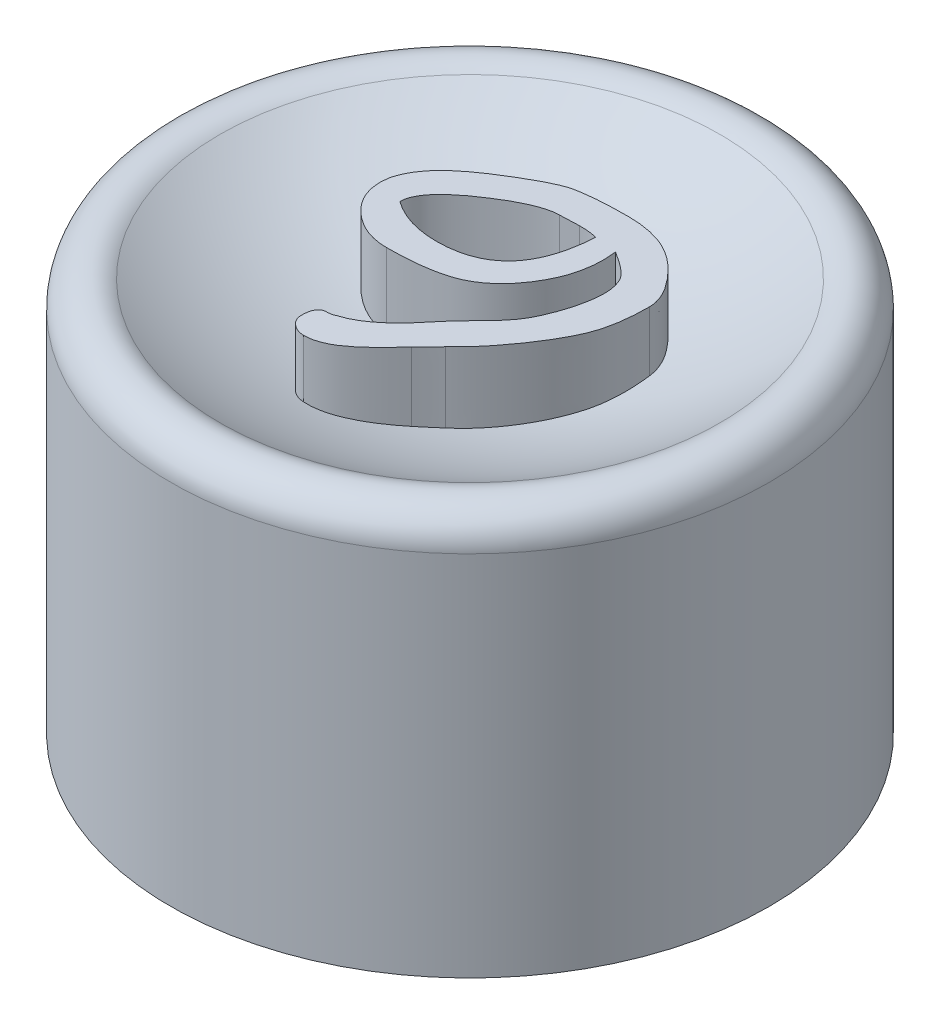
SolidWorks part; units mm, degrees
ref_plane "Front Plane" through (0, 0, 0) normal (0, 0, 1) x (1, 0, 0)
ref_plane "Top Plane" through (0, 0, 0) normal (0, 1, 0) x (1, 0, 0)
ref_plane "Right Plane" through (0, 0, 0) normal (1, 0, 0) x (0, 0, -1)
sketch "Sketch1" plane through (0, 0, 0) normal (0, 0, 1) x (1, 0, 0)
  line L0 (0, 0) -> (0, -66.4851) construction
  line L1 (55, 0) -> (-55, 0) construction
  line L2 (-1.5494, 0) -> (-1.5494, 3.048)
  line L3 (-1.5494, 3.048) -> (-0.762, 3.048)
  line L4 (-0.762, 3.048) -> (-0.762, 4.064)
  line L5 (-0.762, 4.064) -> (0, 4.064)
  line L6 (0, -55) -> (0, 55) construction
  line L7 (0, 4.064) -> (0, 5.08)
  line L8 (-4.7625, 5.842) -> (-4.7625, 0)
  line L9 (-4.7625, 0) -> (-3.4925, 0)
  line L10 (-3.4925, 0) -> (-3.4925, 4.064)
  line L11 (-3.4925, 4.064) -> (-2.0574, 4.064)
  line L12 (-2.0574, 4.064) -> (-2.0574, 0)
  line L13 (-2.0574, 0) -> (-1.5494, 0)
  line L14 (0, 5.08) -> (3.3062, 5.08) construction
  arc A0 (-4.7625, 5.842) -> (-3.976, 6.2669) centre (-4.2545, 5.842) cw
  arc A1 (-3.976, 6.2669) -> (0, 5.08) centre (0, 12.3333) ccw
  dimension "D4" = 1.524
  dimension "D5" = 6.35
  dimension "D9" = 0.508
  dimension "D1" = 9.525
  dimension "D2" = 3.0988
  dimension "D3" = 3.048
  dimension "D6" = 0.508
  dimension "D7" = 1.016
  dimension "D8" = 1.27
  dimension "D10" = 5.08
revolve "Revolve1" add sketch "Sketch1" angle 360 about L0
ref_plane "Plane1" through (0, 6.35, 0) normal (0, 1, 0) x (-1, 0, 0)
sketch "Sketch3" plane through (0, 6.35, 0) normal (0, 1, 0) x (-1, 0, 0)
  line L0 (-2.3812, -2.032) -> (2.3813, -2.032) construction
  line L1 (0, 0) -> (0, -7.9672) construction
  line L2 (0, 3.4925) -> (0, -3.4925) construction
  line L3 (3.4925, 0) -> (-3.4925, 0) construction
  text T0 "6" font "Segoe Print" height 4.7625
  dimension "D1" = 2.032
  dimension "D2" = 4.7625
extrude "Boss-Extrude1" add sketch "Sketch3" against normal up to surface (0.917 mm away)
